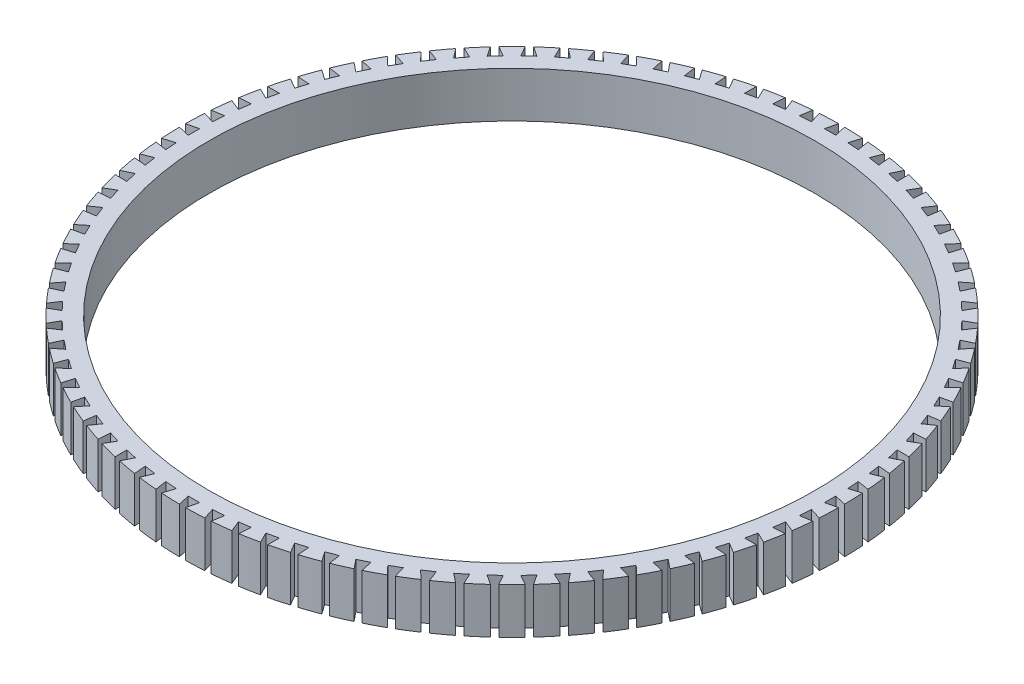
SolidWorks part; units mm, degrees
ref_plane "Front Plane" through (0, 0, 0) normal (0, 0, 1) x (1, 0, 0)
ref_plane "Top Plane" through (0, 0, 0) normal (0, 1, 0) x (1, 0, 0)
ref_plane "Right Plane" through (0, 0, 0) normal (1, 0, 0) x (0, 0, -1)
sketch "Sketch1" plane through (0, 0, 0) normal (0, 1, 0) x (1, 0, 0)
  circle A0 centre (0, 0) radius 39.7
  circle A1 centre (0, 0) radius 36.5
  dimension "D1" = 3.2
  dimension "D2" = 73
extrude "Boss-Extrude1" add sketch "Sketch1" along normal blind 5.5
sketch "Sketch2" plane through (0, 0, 0) normal (0, 1, 0) x (1, 0, 0)
  line L0 (0, 39.7) -> (0, 0) construction
  line L1 (0.6847, 38.3247) -> (-0.6847, 38.3247)
  line L2 (-0.6847, 38.3247) -> (-0.359, 39.7)
  line L3 (-0.359, 39.7) -> (-0.359, 41.5528)
  line L4 (-0.359, 41.5528) -> (0.359, 41.5528)
  line L5 (0.359, 39.7) -> (0.359, 41.5528)
  line L6 (0.6847, 38.3247) -> (0.359, 39.7)
  circle A0 centre (0, 0) radius 39.7 construction
  point P5 (0, 0)
  point P11 (0, 41.5528)
  point P13 (0, 38.3247)
  point P14 (0, 0)
  dimension "D1" = 0.6847
  dimension "D2" = 1.3753
  dimension "D3" = 0.3256
  dimension "D4" = 1.8528
extrude "Cut-Extrude1" cut sketch "Sketch2" along normal through all
pattern_circular "CirPattern1" count 84 over 360 about axis through (0, 0, 0) along (0, 1, 0) of "Cut-Extrude1"
